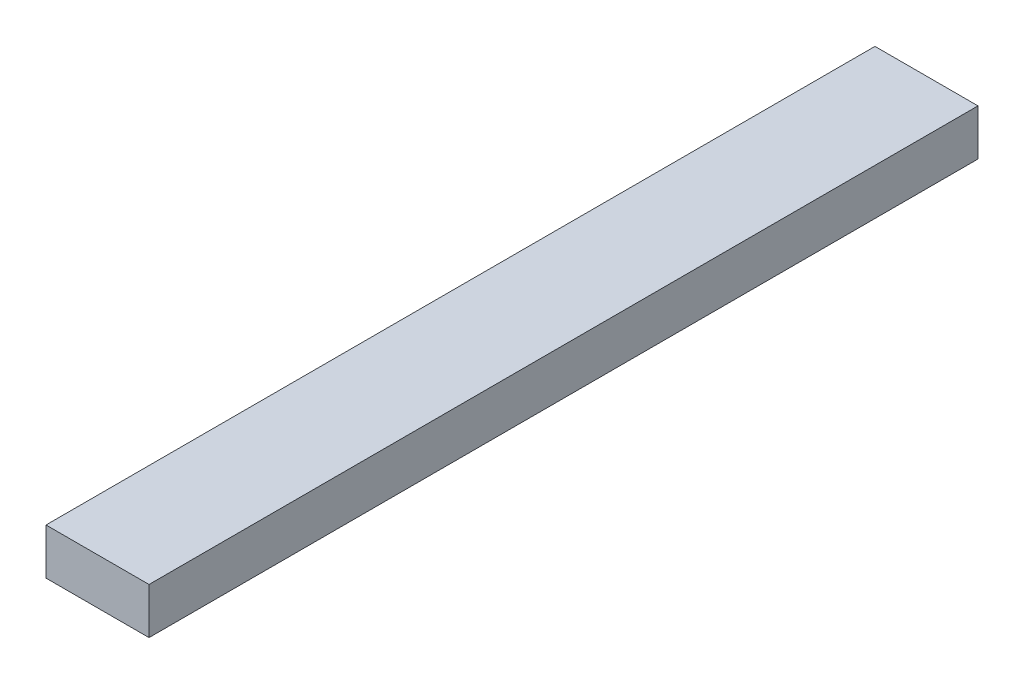
SolidWorks part; units mm, degrees
ref_plane "Front Plane" through (0, 0, 0) normal (1, 0, 0) x (0, 1, 0)
ref_plane "Top Plane" through (0, 0, 0) normal (0, 0, 1) x (0, 1, 0)
ref_plane "Right Plane" through (0, 0, 0) normal (0, 1, 0) x (-1, 0, 0)
sketch "Sketch1" plane through (0, 0, 0) normal (0, 0, 1) x (0, 1, 0)
  line L1 (-8.3312, -18.6436) -> (8.3312, -18.6436)
  line L2 (-8.3312, -18.6436) -> (-8.3312, 18.6436)
  line L3 (-8.3312, 18.6436) -> (8.3312, 18.6436)
  line L4 (8.3312, -18.6436) -> (8.3312, 18.6436)
  line L5 (-8.3312, -18.6436) -> (8.3312, 18.6436) construction
  line L6 (-8.3312, 18.6436) -> (8.3312, -18.6436) construction
  point P0 (0, 0)
  dimension "D1" = 16.6624
  dimension "D2" = 37.2872
extrude "Boss-Extrude1" add sketch "Sketch1" along normal mid plane 300
